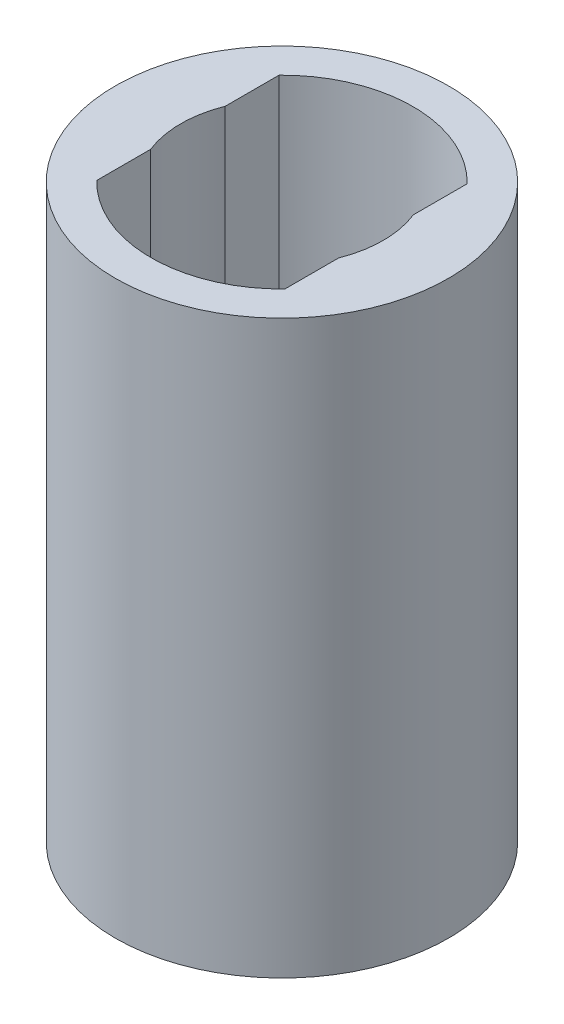
SolidWorks part; units mm, degrees
ref_plane "前视基准面" through (0, 0, 0) normal (0, 0, 1) x (1, 0, 0)
ref_plane "上视基准面" through (0, 0, 0) normal (0, 1, 0) x (1, 0, 0)
ref_plane "右视基准面" through (0, 0, 0) normal (1, 0, 0) x (0, 0, -1)
other "Configuration Table"
sketch "草图1" plane through (0, 0, 0) normal (0, 1, 0) x (1, 0, 0)
  circle A0 centre (0, 0) radius 3.5
  dimension "D1" = 7
extrude "凸台-拉伸1" add sketch "草图1" along normal blind 12
sketch "草图2" plane through (0, 12, 0) normal (0, 1, 0) x (1, 0, 0)
  circle A0 centre (0, 0) radius 2.125
  dimension "D1" = 4.25
extrude "切除-拉伸1" cut sketch "草图2" against normal blind 12
sketch "草图3" plane through (0, 0, 0) normal (1, 0, 0) x (0, 0, -1)
  circle A0 centre (0, 2.6922) radius 1.5
  point P2 (0, 2.6922)
  dimension "D1" = 3
extrude "切除-拉伸2" cut sketch "草图3" against normal blind 12
sketch "草图4" plane through (0, 12, 0) normal (0, 1, 0) x (1, 0, 0)
  line L0 (0, 4.0327) -> (0, -4.0327) construction
  line L2 (-1.975, 1.9136) -> (-1.975, -1.9136)
  line L4 (1.975, 1.9136) -> (1.975, -1.9136)
  line L5 (-1.975, 1.9136) -> (1.975, -1.9136) construction
  line L6 (-1.975, -1.9136) -> (1.975, 1.9136) construction
  arc A0 (-1.975, -1.9136) -> (1.975, -1.9136) centre (0, 0) ccw
  arc A1 (1.975, 1.9136) -> (-1.975, 1.9136) centre (0, 0) ccw
  point P10 (0, 0)
  dimension "D1" = 5.5
  dimension "D2" = 3.95
extrude "切除-拉伸3" cut sketch "草图4" against normal blind 5 contours A1 L2 A0 L4
